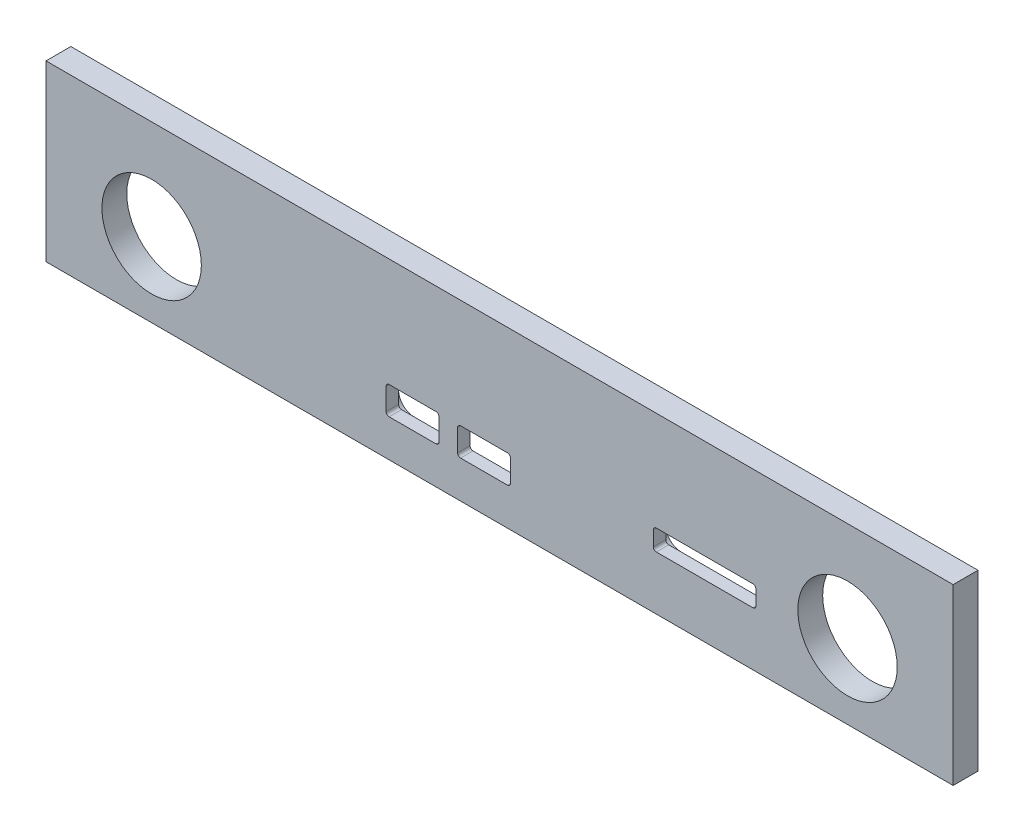
SolidWorks part; units mm, degrees
material "MDF"
ref_plane "Front Plane" through (0, 0, 0) normal (0, 0, 1) x (1, 0, 0)
ref_plane "Top Plane" through (0, 0, 0) normal (0, 1, 0) x (1, 0, 0)
ref_plane "Right Plane" through (0, 0, 0) normal (1, 0, 0) x (0, 0, -1)
sketch "Sketch1" plane through (0, 0, 0) normal (0, 0, 1) x (1, 0, 0)
  line L1 (-115.8875, -22.225) -> (115.8875, -22.225)
  line L2 (-115.8875, -22.225) -> (-115.8875, 22.225)
  line L3 (-115.8875, 22.225) -> (115.8875, 22.225)
  line L4 (115.8875, -22.225) -> (115.8875, 22.225)
  line L5 (-115.8875, -22.225) -> (115.8875, 22.225) construction
  line L6 (-115.8875, 22.225) -> (115.8875, -22.225) construction
  point P0 (0, 0)
  dimension "D1" = 44.45
  dimension "D2" = 231.775
extrude "Boss-Extrude1" add sketch "Sketch1" along normal blind 6.35
sketch "Sketch2" plane through (0, 0, 6.35) normal (0, 0, 1) x (1, 0, 0)
  line L12 (-28.9719, -5.5563) -> (-28.9719, -12.7)
  line L13 (-15.4781, -5.5563) -> (-28.9719, -5.5563)
  line L14 (-15.4781, -12.7) -> (-15.4781, -5.5563)
  line L15 (-28.9719, -12.7) -> (-15.4781, -12.7)
  line L16 (-10.7156, -12.7) -> (2.7781, -12.7)
  line L17 (-10.7156, -5.5563) -> (-10.7156, -12.7)
  line L18 (2.7781, -12.7) -> (2.7781, -5.5563)
  line L19 (2.7781, -5.5563) -> (-10.7156, -5.5563)
  line L20 (39.2906, -8.4773) -> (65.4844, -8.4773)
  line L21 (39.2906, -3.175) -> (39.2906, -8.4773)
  line L22 (65.4844, -3.175) -> (39.2906, -3.175)
  line L23 (65.4844, -8.4773) -> (65.4844, -3.175)
  line L24 (-115.8875, -22.225) -> (115.8875, -22.225) construction
  line L25 (-115.8875, 22.225) -> (-115.8875, -22.225) construction
  line L26 (115.8875, -22.225) -> (115.8875, 22.225) construction
  circle A2 centre (88.9, -3.175) radius 12.7
  circle A3 centre (-88.9, -3.175) radius 12.7
  dimension "D13" = 19.05
  dimension "D14" = 25.4
  dimension "D15" = 25.4
  dimension "D1" = 9.525
  dimension "D2" = 86.9156
  dimension "D3" = 13.4937
  dimension "D4" = 105.1719
  dimension "D5" = 7.1438
  dimension "D6" = 155.1781
  dimension "D7" = 26.1938
  dimension "D8" = 13.7477
  dimension "D9" = 5.3023
  dimension "D10" = 19.05
  dimension "D11" = 26.9875
  dimension "D12" = 26.9875
extrude "Cut-Extrude1" cut sketch "Sketch2" against normal up to next
fillet "Fillet1" radius 0.762 12 edges at (65.4844, -3.175, 3.175) (39.2906, -3.175, 3.175) (39.2906, -8.4773, 3.175) (65.4844, -8.4773, 3.175) (2.7781, -12.7, 3.175) (-10.7156, -12.7, 3.175) (-10.7156, -5.5563, 3.175) (2.7781, -5.5563, 3.175) (-15.4781, -5.5563, 3.175) (-15.4781, -12.7, 3.175) (-28.9719, -12.7, 3.175) (-28.9719, -5.5563, 3.175)
sketch "Sketch3" plane through (0, 0, 0) normal (0, 0, -1) x (-1, 0, 0)
  line L24 (-64.7224, -11.6523) -> (-40.0526, -11.6523)
  line L25 (-36.1156, -7.7153) -> (-36.1156, -3.937)
  line L26 (-40.0526, 0) -> (-64.7224, 0)
  line L27 (-68.6594, -3.937) -> (-68.6594, -7.7153)
  line L28 (-64.7224, -11.6523) -> (-40.0526, -11.6523)
  line L29 (-36.1156, -7.7153) -> (-36.1156, -3.937)
  line L30 (-40.0526, 0) -> (-64.7224, 0)
  line L31 (-68.6594, -3.937) -> (-68.6594, -7.7153)
  arc A20 (-68.6594, -7.7153) -> (-64.7224, -11.6523) centre (-64.7224, -7.7153) ccw
  arc A21 (-40.0526, -11.6523) -> (-36.1156, -7.7153) centre (-40.0526, -7.7153) ccw
  arc A22 (-36.1156, -3.937) -> (-40.0526, 0) centre (-40.0526, -3.937) ccw
  arc A23 (-64.7224, 0) -> (-68.6594, -3.937) centre (-64.7224, -3.937) ccw
  arc A24 (-68.6594, -7.7153) -> (-64.7224, -11.6523) centre (-64.7224, -7.7153) ccw
  arc A25 (-40.0526, -11.6523) -> (-36.1156, -7.7153) centre (-40.0526, -7.7153) ccw
  arc A26 (-36.1156, -3.937) -> (-40.0526, 0) centre (-40.0526, -3.937) ccw
  arc A27 (-64.7224, 0) -> (-68.6594, -3.937) centre (-64.7224, -3.937) ccw
  dimension "D1" = 3.175
extrude "Cut-Extrude2" cut sketch "Sketch3" against normal blind 3.175
sketch "Sketch4" plane through (0, 0, 0) normal (0, 0, -1) x (-1, 0, 0)
  line L23 (32.1469, -11.938) -> (32.1469, -6.3183)
  line L24 (9.9536, -15.875) -> (-2.0161, -15.875)
  line L25 (-2.0161, -2.3813) -> (9.9536, -2.3813)
  line L26 (-5.9531, -11.938) -> (-5.9531, -6.3183)
  line L27 (28.2099, -15.875) -> (-2.0161, -15.875)
  line L28 (-2.0161, -2.3813) -> (28.2099, -2.3813)
  line L29 (-5.9531, -11.938) -> (-5.9531, -6.3183)
  line L30 (32.1469, -11.938) -> (32.1469, -6.3183)
  arc A16 (-5.9531, -11.938) -> (-2.0161, -15.875) centre (-2.0161, -11.938) ccw
  arc A17 (-2.0161, -2.3813) -> (-5.9531, -6.3183) centre (-2.0161, -6.3183) ccw
  arc A18 (-5.9531, -11.938) -> (-2.0161, -15.875) centre (-2.0161, -11.938) ccw
  arc A19 (-2.0161, -2.3813) -> (-5.9531, -6.3183) centre (-2.0161, -6.3183) ccw
  arc A22 (28.2099, -15.875) -> (32.1469, -11.938) centre (28.2099, -11.938) ccw
  arc A23 (32.1469, -6.3183) -> (28.2099, -2.3813) centre (28.2099, -6.3183) ccw
  arc A24 (28.2099, -15.875) -> (32.1469, -11.938) centre (28.2099, -11.938) ccw
  arc A25 (32.1469, -6.3183) -> (28.2099, -2.3813) centre (28.2099, -6.3183) ccw
  dimension "D1" = 3.175
  dimension "D2" = 3.175
extrude "Cut-Extrude3" cut sketch "Sketch4" against normal blind 3.175
